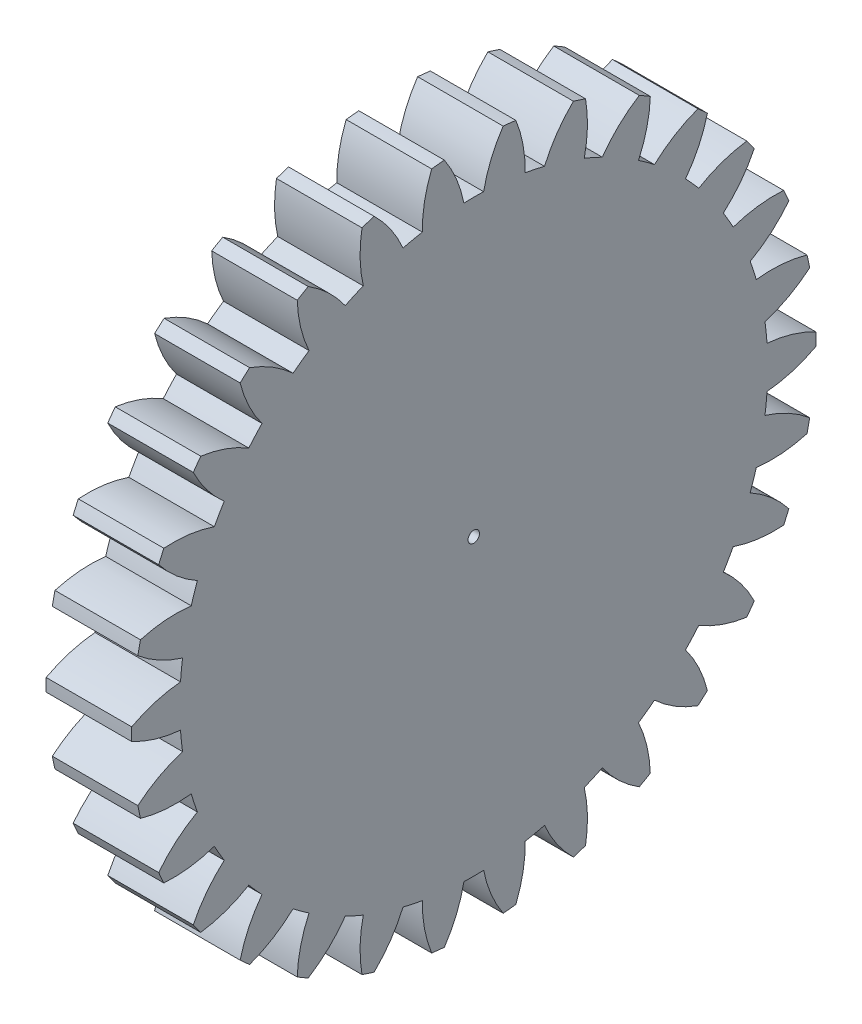
SolidWorks part; units mm, degrees
ref_plane "Plane1" through (0, 0, 0) normal (0, 0, 1) x (1, 0, 0)
ref_plane "Plane2" through (0, 0, 0) normal (0, 1, 0) x (1, 0, 0)
ref_plane "Plane3" through (0, 0, 0) normal (1, 0, 0) x (0, 0, -1)
sketch "HoldingSke" plane through (0, 0, 0) normal (0, 1, 0) x (1, 0, 0)
  line L0 (0, 0) -> (0.5774, -0.3333)
  line L1 (-15, 0) -> (100, 0) construction
  line L2 (0, 0) -> (-2.1039, 2.3779)
  line L3 (0, 0) -> (-11.863, 4.5341)
  line L4 (0, 0) -> (7.479, 4.318)
  line L5 (0, 0) -> (-46.8476, -17.4728)
  line L6 (0, 0) -> (-4.9738, -3.3558)
  line L7 (-2.1039, 2.3779) -> (8.6586, 51.2059)
  line L8 (-76.2, 54.61) -> (-76.1, 54.61)
  line L9 (-71.009, 38.7566) -> (-53.1078, 45.2721)
  line L10 (-76.2, 71.12) -> (104.1128, 71.12)
  line L11 (0, 0) -> (-6, 0)
  line L12 (-76.2, 101.6) -> (-76.147, 101.6)
  line L13 (24.9733, 27.94) -> (52.9518, 28.4284)
  line L14 (24.9733, 27.94) -> (24.9743, 27.94)
  line L15 (24.9733, 27.94) -> (100.4006, 29.5858)
  line L16 (-63.627, -1.5) -> (-12.827, -1.5)
  circle A0 centre (0, 0) radius 0.4
  circle A1 centre (0, 0) radius 20.624
  circle A2 centre (0, 0) radius 37.5
  circle A3 centre (0, 0) radius 0.4
  dimension "MHD" = 41.248
  dimension "Hub_dia" = 75
  dimension "Bore" = 0.8
  dimension "MBD" = 0.8
  dimension "Num_teeth" = 30
  dimension "Pitch_radius" = 180.3128
  dimension "Pitch" = 0.6667
  dimension "Width" = 6
  dimension "Overall_len" = 50
  dimension "Show_teeth" = 30
  dimension "Thickness" = 6
  dimension "OAL" = 50.0001
  dimension "T_dim" = 0.1
  dimension "Ap" = 20
  dimension "H" = 19.05
  dimension "Backlash" = 0.053
  dimension "Addendum_fac" = 1
  dimension "Dedendum_fac" = 1.25
  dimension "Clearance_fac" = 0.25
  dimension "Dedendum_add" = 0.001
  dimension "Module" = 1.5
sketch "BasProSke" plane through (0, 0, 0) normal (0, 1, 0) x (1, 0, 0)
  line L0 (-10, 0) -> (60, 0) construction
  line L1 (0, 0) -> (0, 24)
  line L2 (0, 0) -> (6, 0)
  line L3 (6, 0) -> (6, 24)
  line L4 (6, 24) -> (0, 24)
  dimension "Diameter" = 48
  dimension "Thickness" = 6
revolve "Base-Revolve" add sketch "BasProSke" angle 360 about L0
sketch "TooCutSke" plane through (0, 0, 0) normal (1, 0, 0) x (0, 0, -1)
  line L1 (0, 0) -> (0, 107) construction
  line L2 (0, 0) -> (-1.2703, 22.4641) construction
  line L3 (0, 0) -> (-4.6983, 44.7014) construction
  line L4 (-1.2703, 22.4641) -> (-2.3492, 22.3507) construction
  arc A0 (0.6933, 20.6123) -> (-0.6933, 20.6123) centre (0, 0) ccw
  arc A1 (2.0805, 23.9351) -> (-2.0805, 23.9351) centre (0, 0) ccw
  circle A2 centre (0, 0) radius 22.5 construction
  circle A3 centre (0, 0) radius 21.1431 construction
  arc A4 (-0.6933, 20.6123) -> (-2.0805, 23.9351) centre (-9.5243, 18.8764) ccw
  arc A5 (2.0805, 23.9351) -> (0.6933, 20.6123) centre (9.5243, 18.8764) ccw
  dimension "Root_dia" = 41.248
  dimension "Overcut_dia" = 48.0508
  dimension "Pitch_dia" = 45
  dimension "Base_dia" = 42.2862
  dimension "Flank_rad" = 9
  dimension "Half_ang" = 6
  dimension "Half_CT" = 1.0848
extrude "ToothCut" cut sketch "TooCutSke" along normal through all
fillet "Breaks" [suppressed] radius 0.03
fillet "RootFillets" [suppressed] radius 0.376
pattern_circular "TeethCuts" count 30 every 12 about axis through (-10, 0, 0) along (1, 0, 0) of "ToothCut", "RootFillets", "Breaks"
sketch "HubNeaOneSke" plane through (0, 0, 0) normal (-1, 0, 0) x (0, 0, 1)
  circle A0 centre (0, 0) radius 20.624
  dimension "Diameter" = 41.248
extrude "HubNearOne" [suppressed] add sketch "HubNeaOneSke" along normal blind 44.0001
sketch "HubNeaBotSke" plane through (0, 0, 0) normal (-1, 0, 0) x (0, 0, 1)
  circle A0 centre (0, 0) radius 20.624
  dimension "Diameter" = 41.248
extrude "HubNearBoth" [suppressed] add sketch "HubNeaBotSke" along normal blind 22
ref_plane "FarPln" through (6, 0, 0) normal (1, 0, 0) x (0, 0, -1)
sketch "HubFarSke" plane through (6, 0, 0) normal (1, 0, 0) x (0, 0, -1)
  circle A0 centre (0, 0) radius 20.624
  dimension "Diameter" = 41.248
extrude "HubFar" [suppressed] add sketch "HubFarSke" along normal blind 22
sketch "BorSke" plane through (0, 0, 0) normal (1, 0, 0) x (0, 0, -1)
  circle A0 centre (0, 0) radius 0.4
  dimension "Diameter" = 0.8
extrude "Bore" cut sketch "BorSke" along normal mid plane 100.0001
sketch "KeySke" plane through (0, 0, 0) normal (1, 0, 0) x (0, 0, -1)
  line L0 (-0.05, 0) -> (-0.05, 0.5)
  line L1 (-0.05, 0.5) -> (0.05, 0.5)
  line L2 (0.05, 0.5) -> (0.05, 0)
  line L3 (0, 0) -> (0, 34) construction
  line L4 (-0.05, 0) -> (0.05, 0)
  dimension "Offset" = 0.5
  dimension "Width" = 0.1
extrude "Keyway" [suppressed] cut sketch "KeySke" along normal mid plane 100.0001
pattern_circular "Keyway2" [suppressed] count 2 every 90 about axis through (-10, 0, 0) along (1, 0, 0)
equation "' \"Module@HoldingSke\" = 6.35"
equation "' \"Num_teeth@HoldingSke\" = 12"
equation "' \"Ap@HoldingSke\" =  20"
equation "' \"Width@HoldingSke\" = 0.5 * 25.4"
equation "' \"Hub_dia@HoldingSke\"= 1 * 25.4"
equation "' \"Overall_len@HoldingSke\" = 1.0 * 25.4"
equation "' \"Bore@HoldingSke\" = 0.75 * 25.4"
equation "' \"T_dim@HoldingSke\" = 0.1 * 25.4"
equation "' \"Width@KeySke\" = 0.25 * 25.4"
equation "' \"Show_teeth@HoldingSke\" = 13"
equation "' \"Backlash@HoldingSke\" = 0.009 * 25.4"
equation "' \"Addendum_fac@HoldingSke\" = 1.0"
equation "' \"Dedendum_fac@HoldingSke\" = 1.25"
equation "' \"Dedendum_add@HoldingSke\" = 0.00005 * 25.4"
equation "' \"Clearance_fac@HoldingSke\" = 0.25"
equation "\"Pitch@HoldingSke\" = 1 / \"Module@HoldingSke\""
equation "\"Overcut_dia@TooCutSke\" = (\"Num_teeth@HoldingSke\" + 2 * \"Addendum_fac@HoldingSke\") / \"Pitch@HoldingSke\" + 0.002 * 25.4"
equation "\"Pitch_dia@TooCutSke\" = \"Num_teeth@HoldingSke\" / \"Pitch@HoldingSke\""
equation "\"Base_dia@TooCutSke\" = \"Num_teeth@HoldingSke\" / \"Pitch@HoldingSke\" * cos((\"Ap@HoldingSke\"  * 3.14159265 / 180))"
equation "\"Root_dia@TooCutSke\" = (\"Num_teeth@HoldingSke\" + 2) / \"Pitch@HoldingSke\" - 2 * (\"Addendum_fac@HoldingSke\" + \"Dedendum_fac@HoldingSke\") / \"Pitch@HoldingSke\" - \"Dedendum_add@HoldingSke\" * 2"
equation "\"Half_ang@TooCutSke\" = 180 / \"Num_teeth@HoldingSke\""
equation "\"Half_CT@TooCutSke\" = \"Num_teeth@HoldingSke\" / \"Pitch@HoldingSke\" * sin((3.14159265 / 2 / \"Num_teeth@HoldingSke\")) / 2 - 7 * \"Backlash@HoldingSke\" / 4"
equation "\"Flank_rad@TooCutSke\" = \"Num_teeth@HoldingSke\" / \"Pitch@HoldingSke\" / 5"
equation "\"Radius@RootFillets\" = \"Clearance_fac@HoldingSke\" / \"Pitch@HoldingSke\" + \"Dedendum_add@HoldingSke\""
equation "\"Break_rad@Breaks\" = 0.02 / \"Pitch@HoldingSke\""
equation "\"Thickness@HoldingSke\" = \"Width@HoldingSke\""
equation "\"OAL@HoldingSke\" = \"Thickness@HoldingSke\""
equation "\"MHD@HoldingSke\" = (\"Num_teeth@HoldingSke\" + 2) / \"Pitch@HoldingSke\" - 2 * (\"Addendum_fac@HoldingSke\" + \"Dedendum_fac@HoldingSke\")  / \"Pitch@HoldingSke\" - \"Dedendum_add@HoldingSke\" * 2"
equation "\"MBD@HoldingSke\" = (\"Num_teeth@HoldingSke\" + 2) / \"Pitch@HoldingSke\" - 2 * (\"Addendum_fac@HoldingSke\" + \"Dedendum_fac@HoldingSke\")  / \"Pitch@HoldingSke\" - \"Dedendum_add@HoldingSke\" * 2 - 0.002 * 25.4"
equation "\"MHD@HoldingSke\" = ((sgn( \"MHD@HoldingSke\" - \"Hub_dia@HoldingSke\" )-1)*( \"MHD@HoldingSke\" - \"Hub_dia@HoldingSke\" ))/-2+ \"Hub_dia@HoldingSke\""
equation "\"MBD@HoldingSke\" = ((sgn( \"MBD@HoldingSke\" - \"Bore@HoldingSke\" )-1)*( \"MBD@HoldingSke\" - \"Bore@HoldingSke\" ))/-2+ \"Bore@HoldingSke\""
equation "\"OAL@HoldingSke\" = ((sgn( \"OAL@HoldingSke\" - \"Overall_len@HoldingSke\" )+1)*( \"OAL@HoldingSke\" - \"Overall_len@HoldingSke\" ))/2 + \"Overall_len@HoldingSke\" + 0.000002 * 25.4"
equation "\"Num_teeth@TeethCuts\" = int( \"Show_teeth@HoldingSke\" ) + 1"
equation "\"Num_teeth@TeethCuts\" = ((sgn( \"Num_teeth@TeethCuts\" - \"Num_teeth@HoldingSke\" )-1)*( \"Num_teeth@TeethCuts\" - \"Num_teeth@HoldingSke\" ))/-2+ \"Num_teeth@HoldingSke\""
equation "\"Num_teeth@TeethCuts\" = ((sgn( \"Num_teeth@TeethCuts\" - 2.0)+1)*( \"Num_teeth@TeethCuts\" - 2.0))/2 +2.0"
equation "\"Angle@TeethCuts\" = 360.0 / \"Num_teeth@HoldingSke\""
equation "\"Diameter@BasProSke\" = (\"Num_teeth@HoldingSke\" + 2 * \"Addendum_fac@HoldingSke\") / \"Pitch@HoldingSke\""
equation "\"Thickness@BasProSke\"  = \"Thickness@HoldingSke\""
equation "' \"Fillet_rad@BasProSke\" =  \"Thickness@HoldingSke\" * 0.05"
equation "\"MHD@HoldingSke\" = ((sgn( \"MHD@HoldingSke\" - \"Root_dia@TooCutSke\" )-1)*( \"MHD@HoldingSke\" - \"Root_dia@TooCutSke\" ))/-2+ \"Root_dia@TooCutSke\""
equation "\"Diameter@HubNeaOneSke\" = \"MHD@HoldingSke\""
equation "\"Length@HubNearOne\" = \"OAL@HoldingSke\" - \"Thickness@BasProSke\""
equation "\"Diameter@HubNeaBotSke\" = \"MHD@HoldingSke\""
equation "\"Length@HubNearBoth\" = ( \"OAL@HoldingSke\" - \"Thickness@BasProSke\" ) / 2.0"
equation "\"Thickness@FarPln\" = \"Thickness@BasProSke\""
equation "\"Diameter@HubFarSke\" = \"MHD@HoldingSke\""
equation "\"Length@HubFar\" = ( \"OAL@HoldingSke\" - \"Thickness@BasProSke\" ) / 2.0"
equation "\"Diameter@BorSke\" = \"MBD@HoldingSke\""
equation "\"D1@Bore\" = \"OAL@HoldingSke\" * 2.0"
equation "\"D1@Keyway\" = \"OAL@HoldingSke\" * 2.0"
equation "\"Offset@KeySke\" = \"T_dim@HoldingSke\" + \"MBD@HoldingSke\" / 2.0"
